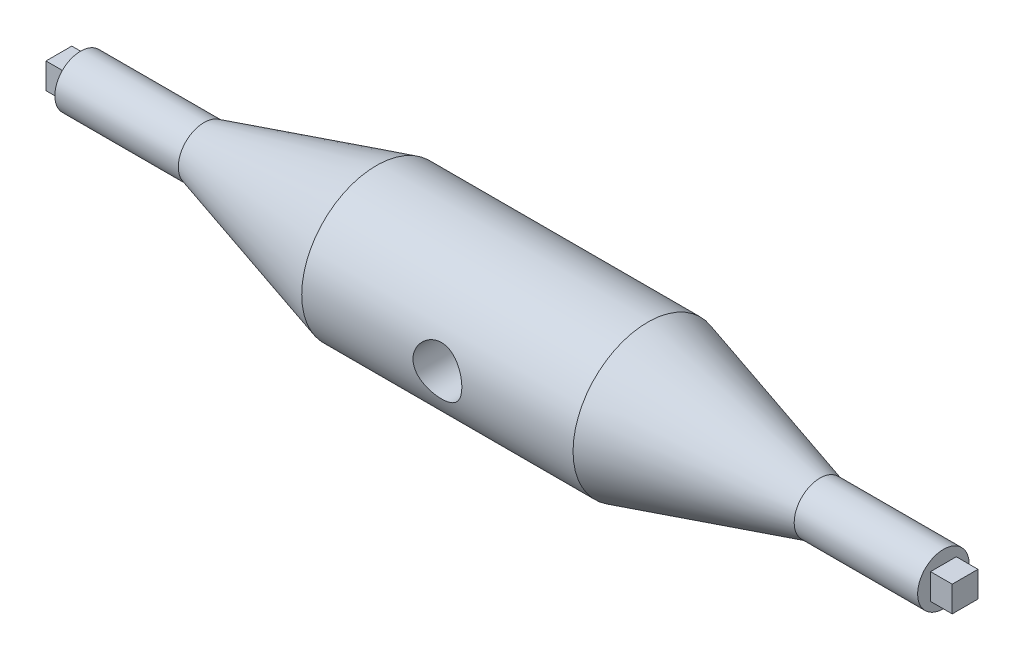
SolidWorks part; units mm, degrees
ref_plane "Plan de face" through (0, 0, 0) normal (0, 0, 1) x (1, 0, 0)
ref_plane "Plan de dessus" through (0, 0, 0) normal (0, 1, 0) x (1, 0, 0)
ref_plane "Plan de droite" through (0, 0, 0) normal (1, 0, 0) x (0, 0, -1)
sketch "Esquisse1" plane through (0, 0, 0) normal (0, 1, 0) x (1, 0, 0)
  line L0 (0, 0) -> (0, 4.75)
  line L1 (0, 4.75) -> (159, 4.75)
  line L2 (159, 4.75) -> (159, 0)
  line L31 (54.5, -9) -> (104.5, -9)
  line L33 (79.5, 4.75) -> (79.5, -9) construction
  line L34 (54.5, 0) -> (54.5, -9) construction
  line L35 (104.5, 0) -> (104.5, -9) construction
  line L36 (22.75, 0) -> (54.5, -9)
  line L37 (104.5, -9) -> (136.25, 0)
  line L38 (0, 0) -> (22.75, 0)
  line L39 (136.25, 0) -> (159, 0)
  dimension "D1" = 159
  dimension "D2" = 9
  dimension "D3" = 9
  dimension "D4" = 4.75
  dimension "D5" = 25
  dimension "D6" = 50
  dimension "D8" = 4.75
revolve "Révolution1" add sketch "Esquisse1" angle 360 about L1
sketch "Esquisse5" plane through (159, 0, 0) normal (1, 0, 0) x (0, 0, -1)
  line L0 (2.375, 2.375) -> (2.375, -2.375)
  line L9 (2.375, 2.375) -> (7.125, 2.375)
  line L10 (7.125, 2.375) -> (7.125, -2.375)
  line L11 (7.125, -2.375) -> (2.375, -2.375)
extrude "Boss.-Extru.3" add sketch "Esquisse5" along normal blind 4
sketch "Esquisse6" plane through (0, 0, 0) normal (-1, 0, 0) x (0, 0, 1)
  line L8 (-4.75, 2.375) -> (-7.125, 2.375)
  line L9 (-7.125, 2.375) -> (-7.125, -2.375)
  line L10 (-7.125, -2.375) -> (-2.375, -2.375)
  line L11 (-2.375, -2.375) -> (-2.375, 2.375)
  line L12 (-2.375, 2.375) -> (-4.75, 2.375)
extrude "Boss.-Extru.4" add sketch "Esquisse6" along normal blind 4
sketch "Esquisse7" plane through (0, 0, -2.375) normal (0, 0, 1) x (1, 0, 0)
  line L0 (0, 0) -> (159, 0) construction
  line L1 (159, 2.375) -> (159, -2.375) construction
  circle A0 centre (79.5, 0) radius 4.5
  dimension "D1" = 9
extrude "Enlèv. mat.-Extru.1" cut sketch "Esquisse7" against normal blind 30 and the other way blind 40
